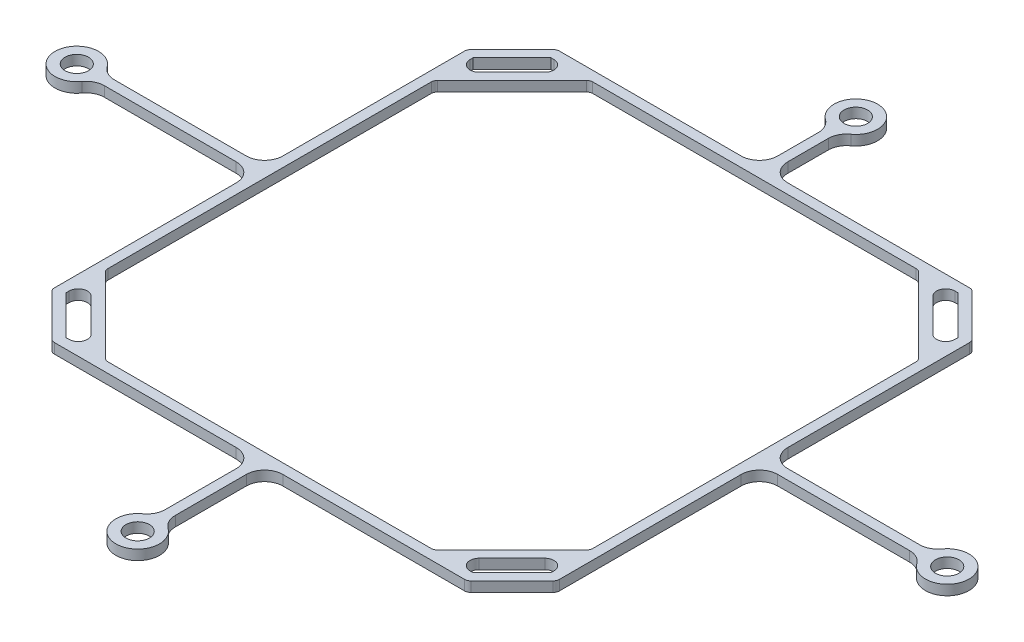
SolidWorks part; units mm, degrees
ref_plane "Front Plane" through (0, 0, 0) normal (0, 0, 1) x (1, 0, 0)
ref_plane "Top Plane" through (0, 0, 0) normal (0, 1, 0) x (1, 0, 0)
ref_plane "Right Plane" through (0, 0, 0) normal (1, 0, 0) x (0, 0, -1)
sketch "Sketch1" plane through (0, 0, 0) normal (0, 1, 0) x (1, 0, 0)
  line L0 (0, 0) -> (0, 56.4488) construction
  line L1 (0, 0) -> (-71.4488, 0) construction
  line L2 (-39.7988, 33.4083) -> (-33.4083, 39.7988)
  line L3 (-33.4083, -39.7988) -> (-29.2929, -39.7988)
  line L4 (-39.7988, -33.4083) -> (-39.7988, -29.2929)
  line L5 (-33.4083, 39.7988) -> (-29.2929, 39.7988)
  line L6 (39.7988, -33.4083) -> (39.7988, -29.2929)
  line L7 (-39.7988, -39.7988) -> (36.6035, 36.6035) construction
  line L8 (-36.6035, 36.6035) -> (39.7988, -39.7988) construction
  line L9 (33.4083, 39.7988) -> (39.7988, 33.4083)
  line L10 (39.7988, -33.4083) -> (33.4083, -39.7988)
  line L11 (-33.4083, -39.7988) -> (-39.7988, -33.4083)
  line L12 (-41.4488, 34.0917) -> (-34.0917, 41.4488)
  line L13 (34.0917, 41.4488) -> (0.825, 41.4488)
  line L14 (34.0917, 41.4488) -> (41.4488, 34.0917)
  line L15 (41.4488, -34.0917) -> (41.4488, -0.825)
  line L16 (41.4488, -34.0917) -> (34.0917, -41.4488)
  line L17 (-34.0917, -41.4488) -> (-0.825, -41.4488)
  line L18 (-34.0917, -41.4488) -> (-41.4488, -34.0917)
  line L19 (-41.4488, 34.0917) -> (-41.4488, 0.825)
  line L20 (-39.7988, 29.2929) -> (-29.2929, 39.7988)
  line L21 (-39.7988, 26.9594) -> (-26.9594, 39.7988)
  line L22 (29.2929, 39.7988) -> (39.7988, 29.2929)
  line L23 (26.9594, 39.7988) -> (39.7988, 26.9594)
  line L24 (39.7988, -29.2929) -> (29.2929, -39.7988)
  line L25 (39.7988, -26.9594) -> (26.9594, -39.7988)
  line L26 (-29.2929, -39.7988) -> (-39.7988, -29.2929)
  line L27 (-26.9594, -39.7988) -> (-39.7988, -26.9594)
  line L28 (-39.7988, 29.2929) -> (-39.7988, 33.4083)
  line L29 (-26.9594, 39.7988) -> (26.9594, 39.7988)
  line L30 (29.2929, 39.7988) -> (33.4083, 39.7988)
  line L31 (39.7988, 29.2929) -> (39.7988, 33.4083)
  line L32 (39.7988, -26.9594) -> (39.7988, 26.9594)
  line L33 (-39.7988, -26.9594) -> (-39.7988, 26.9594)
  line L34 (-26.9594, -39.7988) -> (26.9594, -39.7988)
  line L35 (29.2929, -39.7988) -> (33.4083, -39.7988)
  line L36 (67.9703, -0.825) -> (41.4488, -0.825)
  line L37 (0.825, 52.9703) -> (0.825, 41.4488)
  line L38 (-0.825, 52.9703) -> (-0.825, 41.4488)
  line L39 (67.9703, 0.825) -> (41.4488, 0.825)
  line L40 (-0.825, -57.9703) -> (-0.825, -41.4488)
  line L41 (0.825, -57.9703) -> (0.825, -41.4488)
  line L42 (-67.9703, 0.825) -> (-41.4488, 0.825)
  line L43 (-67.9703, -0.825) -> (-41.4488, -0.825)
  line L44 (0, 0) -> (0, -61.4488) construction
  line L45 (41.4488, 0.825) -> (41.4488, 34.0917)
  line L46 (-0.825, 41.4488) -> (-34.0917, 41.4488)
  line L47 (-41.4488, -0.825) -> (-41.4488, -34.0917)
  line L48 (0.825, -41.4488) -> (34.0917, -41.4488)
  arc A0 (0.825, 52.9703) -> (-0.825, 52.9703) centre (0, 56.4488) ccw
  circle A1 centre (0, 56.4488) radius 1.925
  circle A2 centre (71.4488, 0) radius 1.925
  arc A3 (67.9703, 0.825) -> (67.9703, -0.825) centre (71.4488, 0) cw
  arc A4 (-0.825, -57.9703) -> (0.825, -57.9703) centre (0, -61.4488) ccw
  circle A5 centre (0, -61.4488) radius 1.925
  arc A6 (-67.9703, 0.825) -> (-67.9703, -0.825) centre (-71.4488, 0) ccw
  circle A7 centre (-71.4488, 0) radius 1.925
  point P19 (0, 0)
  point P20 (0, 0)
  point P33 (0, 0)
  point P46 (0, 0)
  point P74 (0, 0)
  dimension "D10" = 3.85
  dimension "D11" = 1.65
  dimension "D15" = 1.65
  dimension "D16" = 3.85
  dimension "D20" = 3.85
  dimension "D21" = 1.65
  dimension "D1" = 1.65
  dimension "D2" = 79.5976
  dimension "D3" = 9.0376
  dimension "D5" = 1.65
  dimension "D6" = 4
  dimension "D7" = 2.91
  dimension "D8" = 1.65
  dimension "D12" = 0.825
  dimension "D13" = 0.825
  dimension "D14" = 15
  dimension "D17" = 30
  dimension "D18" = 0.825
  dimension "D19" = 0.825
  dimension "D22" = 0.825
  dimension "D23" = 0.825
  dimension "D24" = 20
  dimension "D25" = 12.8394
  dimension "D4" = 4
  dimension "D9" = 4
extrude "Boss-Extrude1" add sketch "Sketch1" along normal blind 1.65
fillet "Fillet4" radius 3 16 edges at (0.825, 0.825, -41.4488) (0.825, 0.825, -52.9703) (-0.825, 0.825, -52.9703) (-0.825, 0.825, -41.4488) (67.9703, 0.825, -0.825) (67.9703, 0.825, 0.825) (41.4488, 0.825, -0.825) (41.4488, 0.825, 0.825) (0.825, 0.825, 57.9703) (-0.825, 0.825, 57.9703) (-0.825, 0.825, 41.4488) (0.825, 0.825, 41.4488) (-41.4488, 0.825, 0.825) (-41.4488, 0.825, -0.825) (-67.9703, 0.825, 0.825) (-67.9703, 0.825, -0.825)
fillet "Fillet3" radius 1.5 8 edges at (29.2929, 0.825, 39.7988) (39.7988, 0.825, 29.2929) (-29.2929, 0.825, 39.7988) (-39.7988, 0.825, 29.2929) (-39.7988, 0.825, -29.2929) (-29.2929, 0.825, -39.7988) (39.7988, 0.825, -29.2929) (29.2929, 0.825, -39.7988)
fillet "Fillet5" radius 1 16 edges at (-26.9594, 0.825, 39.7988) (-39.7988, 0.825, 26.9594) (-41.4488, 0.825, 34.0917) (-34.0917, 0.825, 41.4488) (-39.7988, 0.825, -26.9594) (-26.9594, 0.825, -39.7988) (-41.4488, 0.825, -34.0917) (-34.0917, 0.825, -41.4488) (41.4488, 0.825, -34.0917) (34.0917, 0.825, -41.4488) (26.9594, 0.825, -39.7988) (39.7988, 0.825, -26.9594) (34.0917, 0.825, 41.4488) (41.4488, 0.825, 34.0917) (39.7988, 0.825, 26.9594) (26.9594, 0.825, 39.7988)
